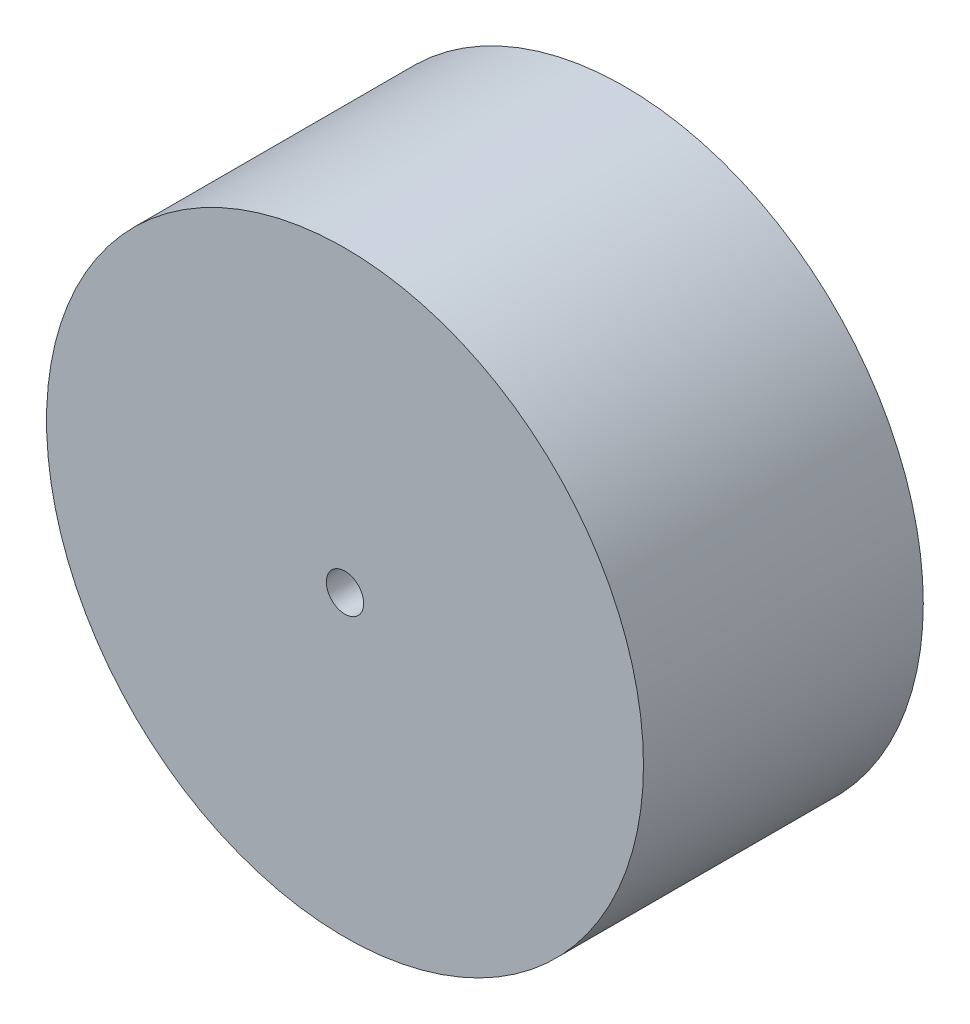
SolidWorks part; units mm, degrees
ref_plane "Front Plane" through (0, 0, 0) normal (0, 0, 1) x (1, 0, 0)
ref_plane "Top Plane" through (0, 0, 0) normal (0, 1, 0) x (1, 0, 0)
ref_plane "Right Plane" through (0, 0, 0) normal (1, 0, 0) x (0, 0, -1)
sketch "Sketch1" plane through (0, 0, 0) normal (0, 0, 1) x (1, 0, 0)
  circle A0 centre (0, 0) radius 40
  dimension "D1" = 80
extrude "Boss-Extrude1" add sketch "Sketch1" against normal blind 37.5
sketch "Sketch2" plane through (0, 0, 0) normal (0, 0, 1) x (1, 0, 0)
  circle A0 centre (0, 0) radius 2.5
  dimension "D1" = 5
extrude "Cut-Extrude1" cut sketch "Sketch2" against normal through all
